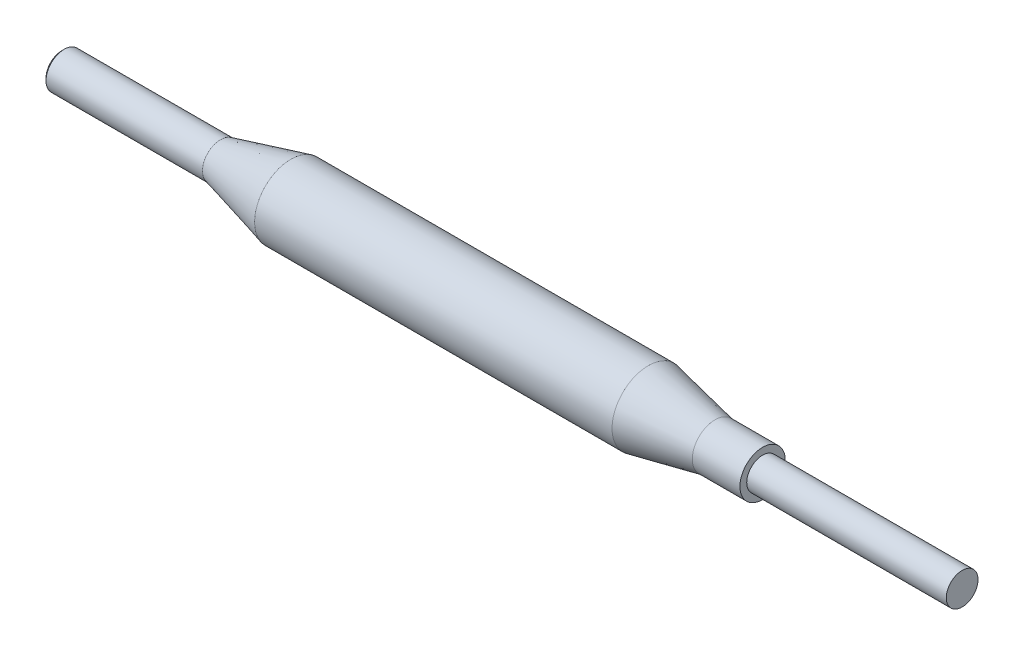
SolidWorks part; units mm, degrees
ref_plane "Ön Düzlem" through (0, 0, 0) normal (0, 0, 1) x (1, 0, 0)
ref_plane "Üst Düzlem" through (0, 0, 0) normal (0, 1, 0) x (1, 0, 0)
ref_plane "Sağ Düzlem" through (0, 0, 0) normal (1, 0, 0) x (0, 0, -1)
sketch "Çizim1" plane through (0, 0, 0) normal (0, 0, 1) x (1, 0, 0)
  line L0 (0, 0) -> (133.3794, 0) construction
  line L1 (0, 0) -> (0, 4)
  line L2 (0, 4) -> (35, 4)
  line L3 (35, 4) -> (50.4919, 8)
  line L4 (50.4919, 8) -> (129.3031, 8)
  line L5 (129.3031, 8) -> (144, 5)
  line L6 (144, 5) -> (154.5, 5)
  line L7 (154.5, 5) -> (154.5, 3.5)
  line L8 (154.5, 3.5) -> (198.5, 3.5)
  line L9 (198.5, 3.5) -> (198.5, 0)
  line L10 (0, 0) -> (198.5, 0)
  point P3 (0, 0)
  point P13 (89.8975, 8)
  point P14 (0, 0)
  point P15 (0, 0)
  dimension "D1" = 198.5
  dimension "D2" = 44
  dimension "D3" = 10.5
  dimension "D4" = 15
  dimension "D5" = 4
  dimension "D6" = 3.5
  dimension "D7" = 5
  dimension "D8" = 8
  dimension "D9" = 16
  dimension "D10" = 35
revolve "Döndür1" add sketch "Çizim1" angle 360 about L0
chamfer "Pah1" distance 0.5 angle 45 1 edges at (0, 0, 4)
